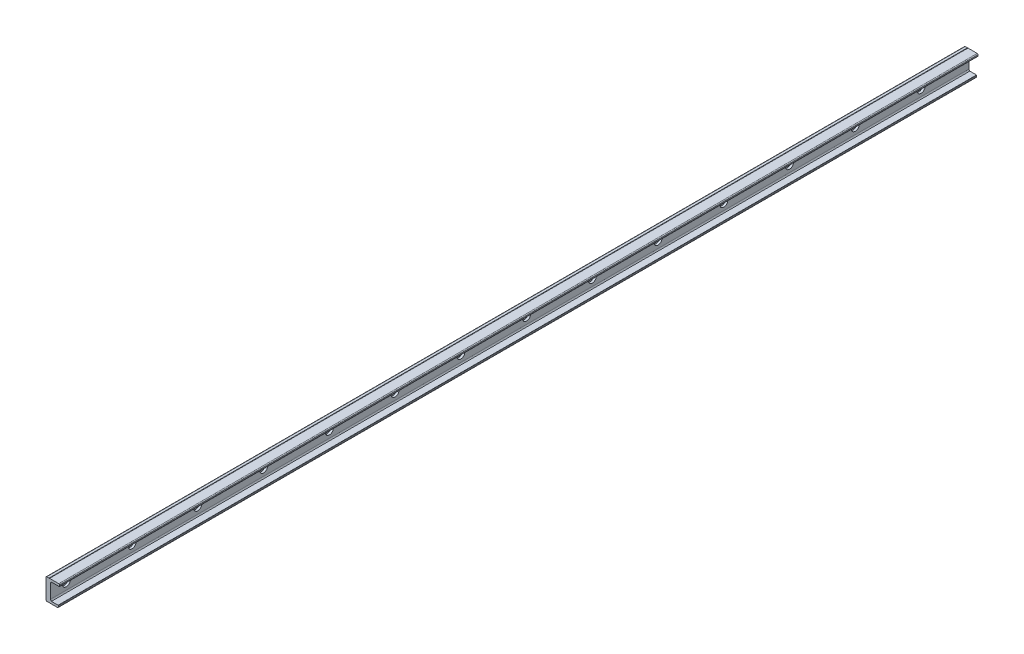
SolidWorks part; units mm, degrees
ref_plane "Front" through (0, 0, 0) normal (0, 0, 1) x (1, 0, 0)
ref_plane "Top" through (0, 0, 0) normal (0, 1, 0) x (1, 0, 0)
ref_plane "Right" through (0, 0, 0) normal (1, 0, 0) x (0, 0, -1)
sketch "Sketch1" plane through (0, 0, 0) normal (0, 0, 1) x (1, 0, 0)
  line L0 (15.494, 12.954) -> (4.394, 12.954)
  line L1 (3.734, 12.954) -> (1.016, 12.954)
  line L2 (0, 11.938) -> (0, -11.938)
  line L3 (1.016, -12.954) -> (13.97, -12.954)
  line L4 (14.986, -11.938) -> (14.986, -10.832)
  line L5 (14.732, -10.16) -> (6.604, -10.16)
  line L6 (5.588, -8.4002) -> (5.588, 8.4002)
  line L7 (6.604, 10.16) -> (14.732, 10.16)
  line L8 (16.51, 10.832) -> (16.51, 11.938)
  line L9 (6.604, 10.16) -> (6.604, 12.954) construction
  line L10 (6.604, -10.16) -> (6.604, -12.954) construction
  line L11 (5.588, 0) -> (0, 0) construction
  line L12 (0, -14.2494) -> (0, 14.2494) construction
  line L13 (9.0805, 0) -> (-9.0805, 0) construction
  arc A0 (3.734, 12.954) -> (4.394, 12.954) centre (4.064, 12.954) ccw
  arc A1 (1.016, 12.954) -> (0, 11.938) centre (1.016, 11.938) ccw
  arc A2 (0, -11.938) -> (1.016, -12.954) centre (1.016, -11.938) ccw
  arc A3 (13.97, -12.954) -> (14.986, -11.938) centre (13.97, -11.938) ccw
  arc A4 (14.986, -10.832) -> (14.732, -10.16) centre (13.97, -10.832) ccw
  arc A5 (5.588, -8.4002) -> (6.604, -10.16) centre (7.62, -8.4002) ccw
  arc A6 (6.604, 10.16) -> (5.588, 8.4002) centre (7.62, 8.4002) ccw
  arc A7 (14.732, 10.16) -> (16.51, 10.832) centre (15.494, 10.832) ccw
  arc A8 (16.51, 11.938) -> (15.494, 12.954) centre (15.494, 11.938) ccw
  dimension "Big Radius" = 2.032
  dimension "Small Radius" = 1.016
  dimension "D4" = 0.33
  dimension "Foot Lg" = 8.382
  dimension "Ht" = 25.908
  dimension "Wd" = 14.986
  dimension "Radius Offset" = 0.254
  dimension "Notch Offset" = 4.064
  dimension "Inner Ht" = 20.32
  dimension "Inner Wd" = 10.922
extrude "Boss-Extrude1" add sketch "Sketch1" along normal mid plane 2438.4
sketch "Sketch2" plane through (5.588, 0, 0) normal (1, 0, 0) x (0, 0, -1)
  line L0 (-1219.2, -8.4002) -> (-1219.2, 8.4002) construction
  circle A0 centre (-1200, 0) radius 4.8895
  dimension "Outer Dia" = 9.779
  dimension "Hole Offset" = 19.2
extrude "Cut-Extrude1" cut sketch "Sketch2" against normal blind 2.794
sketch "Sketch3" plane through (2.794, 0, 0) normal (1, 0, 0) x (0, 0, -1)
  circle A0 centre (-1200, 0) radius 2.8956
  dimension "Inner Dia" = 5.7912
extrude "Cut-Extrude2" cut sketch "Sketch3" against normal through all
pattern_linear "LPattern1" count 31 spacing 80 along (0, 0, -1) of "Cut-Extrude1", "Cut-Extrude2"
sketch "Sketch4" plane through (0, 0, 0) normal (0, 0, 1) x (1, 0, 0)
  line L0 (2.794, -4.8895) -> (2.794, 4.8895) construction
  line L1 (0, -2.8956) -> (2.794, -2.8956) construction
  line L2 (2.794, -4.8895) -> (5.588, -4.8895) construction
  line L3 (5.588, 4.8895) -> (2.794, 4.8895) construction
  line L4 (2.794, 2.8956) -> (0, 2.8956) construction
  line L5 (2.794, -4.8895) -> (2.794, 4.8895)
  line L6 (0, -2.8956) -> (2.794, -2.8956)
  line L7 (2.794, -4.8895) -> (5.588, -4.8895)
  line L8 (5.588, 4.8895) -> (2.794, 4.8895)
  line L9 (2.794, 2.8956) -> (0, 2.8956)
sketch "Sketch5" plane through (0, 0, -1219.2) normal (0, 0, -1) x (-1, 0, 0)
  line L9 (-16.51, 11.938) -> (-16.51, 10.832)
  line L10 (-14.732, 10.16) -> (-6.604, 10.16)
  line L11 (-5.588, 8.4002) -> (-5.588, -8.4002)
  line L12 (-6.604, -10.16) -> (-14.732, -10.16)
  line L13 (-14.986, -10.832) -> (-14.986, -11.938)
  line L14 (-13.97, -12.954) -> (-1.016, -12.954)
  line L15 (0, -11.938) -> (0, 11.938)
  line L16 (-1.016, 12.954) -> (-3.734, 12.954)
  line L17 (-4.394, 12.954) -> (-15.494, 12.954)
  line L18 (-16.51, 11.938) -> (-16.51, 10.832)
  line L19 (-14.732, 10.16) -> (-6.604, 10.16)
  line L20 (-5.588, 8.4002) -> (-5.588, -8.4002)
  line L21 (-6.604, -10.16) -> (-14.732, -10.16)
  line L22 (-14.986, -10.832) -> (-14.986, -11.938)
  line L23 (-13.97, -12.954) -> (-1.016, -12.954)
  line L24 (0, -11.938) -> (0, 11.938)
  line L25 (-1.016, 12.954) -> (-3.734, 12.954)
  line L26 (-4.394, 12.954) -> (-15.494, 12.954)
  arc A9 (-15.494, 12.954) -> (-16.51, 11.938) centre (-15.494, 11.938) ccw
  arc A10 (-16.51, 10.832) -> (-14.732, 10.16) centre (-15.494, 10.832) ccw
  arc A11 (-5.588, 8.4002) -> (-6.604, 10.16) centre (-7.62, 8.4002) ccw
  arc A12 (-6.604, -10.16) -> (-5.588, -8.4002) centre (-7.62, -8.4002) ccw
  arc A13 (-14.732, -10.16) -> (-14.986, -10.832) centre (-13.97, -10.832) ccw
  arc A14 (-14.986, -11.938) -> (-13.97, -12.954) centre (-13.97, -11.938) ccw
  arc A15 (-1.016, -12.954) -> (0, -11.938) centre (-1.016, -11.938) ccw
  arc A16 (0, 11.938) -> (-1.016, 12.954) centre (-1.016, 11.938) ccw
  arc A17 (-4.394, 12.954) -> (-3.734, 12.954) centre (-4.064, 12.954) ccw
  arc A18 (-15.494, 12.954) -> (-16.51, 11.938) centre (-15.494, 11.938) ccw
  arc A19 (-16.51, 10.832) -> (-14.732, 10.16) centre (-15.494, 10.832) ccw
  arc A20 (-5.588, 8.4002) -> (-6.604, 10.16) centre (-7.62, 8.4002) ccw
  arc A21 (-6.604, -10.16) -> (-5.588, -8.4002) centre (-7.62, -8.4002) ccw
  arc A22 (-14.732, -10.16) -> (-14.986, -10.832) centre (-13.97, -10.832) ccw
  arc A23 (-14.986, -11.938) -> (-13.97, -12.954) centre (-13.97, -11.938) ccw
  arc A24 (-1.016, -12.954) -> (0, -11.938) centre (-1.016, -11.938) ccw
  arc A25 (0, 11.938) -> (-1.016, 12.954) centre (-1.016, 11.938) ccw
  arc A26 (-4.394, 12.954) -> (-3.734, 12.954) centre (-4.064, 12.954) ccw
  dimension "D1" = 0
extrude "Cut-Extrude3" cut sketch "Sketch5" against normal offset from surface (1320.8 mm away) 1117.6 up to face at (8.6826, 1.3882, 1219.2)
